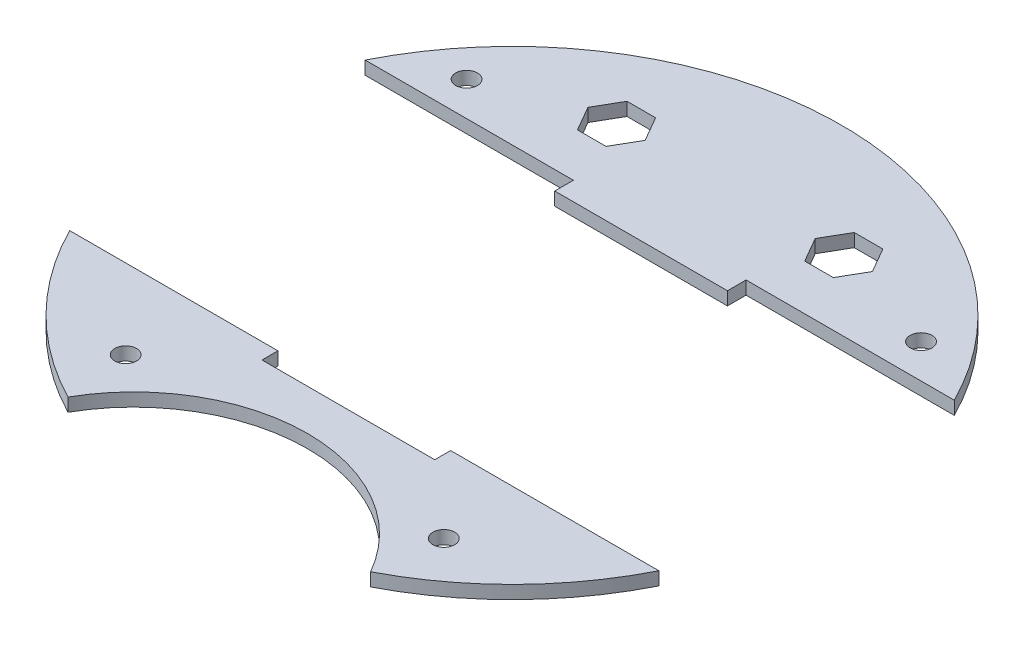
SolidWorks part; units mm, degrees
material "Acrylic (Medium-high impact)"
ref_plane "Front Plane" through (0, 0, 0) normal (0, 0, 1) x (1, 0, 0)
ref_plane "Top Plane" through (0, 0, 0) normal (0, 1, 0) x (1, 0, 0)
ref_plane "Right Plane" through (0, 0, 0) normal (1, 0, 0) x (0, 0, -1)
sketch "Sketch1" plane through (0, 0, 0) normal (0, 1, 0) x (1, 0, 0)
  line L0 (0, -83.2398) -> (-33.2911, -64.4046) construction
  line L1 (0, -83.2398) -> (0, 0) construction
  arc A0 (33.2911, -64.4046) -> (-33.2911, -64.4046) centre (0, 0) ccw
  arc A1 (33.2911, -64.4046) -> (-33.2911, -64.4046) centre (0, -83.2398) ccw
  dimension "D1" = 145
  dimension "D2" = 76.5
  dimension "D3" = 60.5
extrude "Boss-Extrude1" add sketch "Sketch1" along normal blind 2.9
sketch "solenoid placement" plane through (0, 2.9, 0) normal (0, 1, 0) x (1, 0, 0)
  line L4 (-19, -36) -> (19, -36)
  line L5 (-19, 28.4) -> (-19, -36)
  line L6 (19, 28.4) -> (-19, 28.4)
  line L7 (19, -36) -> (19, 28.4)
  line L8 (-19, -36) -> (19, -36)
  line L9 (-19, 28.4) -> (-19, -36)
  line L10 (19, 28.4) -> (-19, 28.4)
  line L11 (19, -36) -> (19, 28.4)
  dimension "D1" = 0
extrude "Cut-Extrude1" cut sketch "solenoid placement" against normal through all
sketch "Sketch5" plane through (0, 2.9, 0) normal (0, 1, 0) x (1, 0, 0)
  line L6 (-18.7069, 48) -> (-21.8534, 53.45)
  line L7 (-21.8534, 53.45) -> (-28.1466, 53.45)
  line L8 (-28.1466, 53.45) -> (-31.2931, 48)
  line L9 (-31.2931, 48) -> (-28.1466, 42.55)
  line L10 (-28.1466, 42.55) -> (-21.8534, 42.55)
  line L11 (-21.8534, 42.55) -> (-18.7069, 48)
  line L12 (-18.7069, 48) -> (-21.8534, 53.45)
  line L13 (-21.8534, 53.45) -> (-28.1466, 53.45)
  line L14 (-28.1466, 53.45) -> (-31.2931, 48)
  line L15 (-31.2931, 48) -> (-28.1466, 42.55)
  line L16 (-28.1466, 42.55) -> (-21.8534, 42.55)
  line L17 (-21.8534, 42.55) -> (-18.7069, 48)
  line L18 (18.7069, 48) -> (21.8534, 42.55)
  line L19 (21.8534, 53.45) -> (18.7069, 48)
  line L20 (28.1466, 53.45) -> (21.8534, 53.45)
  line L21 (31.2931, 48) -> (28.1466, 53.45)
  line L22 (28.1466, 42.55) -> (31.2931, 48)
  line L23 (21.8534, 42.55) -> (28.1466, 42.55)
  line L24 (18.7069, 48) -> (21.8534, 42.55)
  line L25 (21.8534, 53.45) -> (18.7069, 48)
  line L26 (28.1466, 53.45) -> (21.8534, 53.45)
  line L27 (31.2931, 48) -> (28.1466, 53.45)
  line L28 (28.1466, 42.55) -> (31.2931, 48)
  line L29 (21.8534, 42.55) -> (28.1466, 42.55)
  dimension "D1" = 0
  dimension "D2" = 0
extrude "Cut-Extrude5" cut sketch "Sketch5" against normal through all
sketch "Sketch6" plane through (0, 2.9, 0) normal (0, 1, 0) x (1, 0, 0)
  circle A1 centre (35, -50) radius 2.4
  circle A2 centre (35, -50) radius 2.4
  circle A3 centre (-35, -50) radius 2.4
  circle A4 centre (-35, -50) radius 2.4
  circle A5 centre (-50, 40) radius 2.4
  circle A6 centre (-50, 40) radius 2.4
  circle A7 centre (50, 40) radius 2.4
  circle A8 centre (50, 40) radius 2.4
  dimension "D1" = 0
  dimension "D2" = 0
  dimension "D3" = 0
  dimension "D4" = 0
extrude "Cut-Extrude6" cut sketch "Sketch6" against normal through all
sketch "Sketch3" plane through (0, 2.9, 0) normal (0, 1, 0) x (1, 0, 0)
  line L0 (-19, 28.4) -> (-19, 32.5)
  line L1 (72.5, -32.5) -> (-72.5, -32.5)
  line L2 (72.5, -32.5) -> (72.5, 32.5)
  line L3 (72.5, 32.5) -> (19, 32.5)
  line L4 (-72.5, -32.5) -> (-72.5, 32.5)
  line L5 (72.5, -32.5) -> (-72.5, 32.5) construction
  line L6 (72.5, 32.5) -> (-72.5, -32.5) construction
  line L7 (-19, 28.4) -> (19, 28.4)
  line L8 (19, 28.4) -> (19, 32.5)
  line L9 (-19, 32.5) -> (-72.5, 32.5)
  arc A0 (33.2911, -64.4046) -> (-33.2911, -64.4046) centre (0, 0) ccw construction
  point P0 (0, 0)
  dimension "D1" = 65
extrude "Cut-Extrude3" cut sketch "Sketch3" against normal through all
equation "\"smallPulleyTeeth\"= 15"
equation "\"largePulleyTeeth\"= 30"
equation "\"eighthThick\"= 2.9mm"
equation "\"sixteenthThick\" = 1.7mm"
equation "\"quarterThick\"=6.0mm"
equation "\"OD\" = 145mm"
equation "\"puckAngle\" = 60.5deg"
equation "\"D1@Sketch1\"=\"OD\""
equation "\"puckDiam\" = 76.5mm"
equation "\"D2@Sketch1\"=\"puckDiam\""
equation "\"D3@Sketch1\"=\"puckAngle\""
equation "\"D1@Boss-Extrude1\"=\"eighthThick\""
equation "\"axlePress\" = 5.9mm"
equation "\"press\" = 0.2mm"
equation "\"wheelClear\" = 0.3mm"
equation "\"10-32clear\" = 4.8mm"
equation "\"6-32clear\" = 3.3mm"
equation "\"8-32clear\" = 4.0mm"
equation "\"wheelHeight\" = 22mm"
equation "\"wheelWell\" = 65mm"
equation "\"D1@Sketch3\"=\"wheelWell\""
